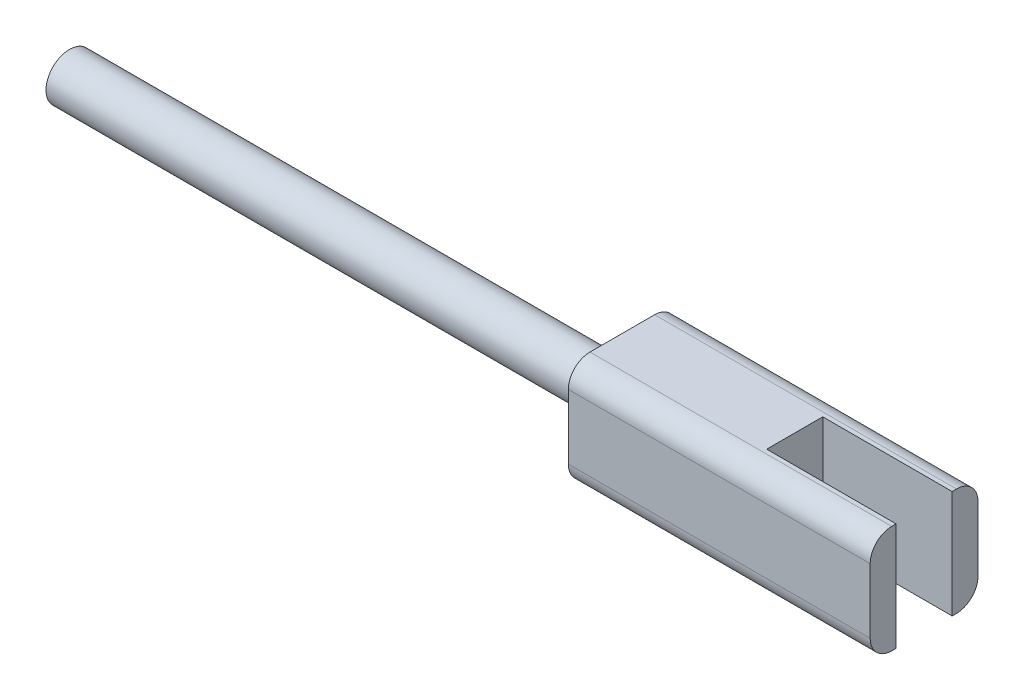
SolidWorks part; units mm, degrees
ref_plane "Front Plane" through (0, 0, 0) normal (0, 0, 1) x (1, 0, 0)
ref_plane "Top Plane" through (0, 0, 0) normal (0, 1, 0) x (1, 0, 0)
ref_plane "Right Plane" through (0, 0, 0) normal (1, 0, 0) x (0, 0, -1)
sketch "Sketch1" plane through (0, 0, 0) normal (1, 0, 0) x (0, 0, -1)
  circle A0 centre (0, 0) radius 1.09
extrude "Boss-Extrude1" add sketch "Sketch1" along normal blind 27.637
ref_plane "Plane1" through (25.637, 0, 0) normal (1, 0, 0) x (0, 0, -1)
sketch "Sketch2" plane through (25.637, 0, 0) normal (1, 0, 0) x (0, 0, -1)
  line L0 (-1.5, -2.5) -> (1.5, -2.5)
  line L1 (2.5, -1.5) -> (2.5, 1.5)
  line L2 (1.5, 2.5) -> (-1.5, 2.5)
  line L3 (-2.5, 1.5) -> (-2.5, -1.5)
  arc A0 (1.5, -2.5) -> (2.5, -1.5) centre (1.5, -1.5) ccw
  arc A1 (2.5, 1.5) -> (1.5, 2.5) centre (1.5, 1.5) ccw
  arc A2 (-1.5, 2.5) -> (-2.5, 1.5) centre (-1.5, 1.5) ccw
  arc A3 (-2.5, -1.5) -> (-1.5, -2.5) centre (-1.5, -1.5) ccw
extrude "Boss-Extrude2" add sketch "Sketch2" along normal blind 14
sketch "Sketch3" plane through (0, 0, 0) normal (0, 1, 0) x (1, 0, 0)
  line L0 (33.637, 1.3) -> (40.637, 1.3)
  line L1 (40.637, 1.3) -> (40.637, -1.3)
  line L2 (40.637, -1.3) -> (33.637, -1.3)
  line L3 (33.637, -1.3) -> (33.637, 1.3)
extrude "Cut-Extrude1" cut sketch "Sketch3" against normal through all and the other way through all
